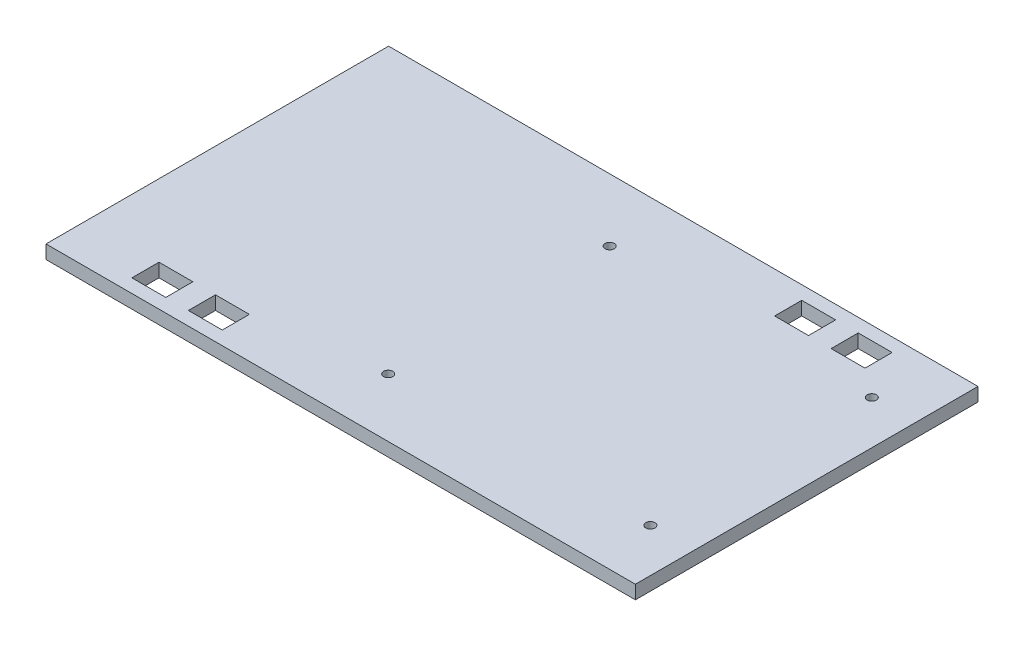
SolidWorks part; units mm, degrees
ref_plane "Front" through (0, 0, 0) normal (0, 0, 1) x (1, 0, 0)
ref_plane "Top" through (0, 0, 0) normal (0, 1, 0) x (1, 0, 0)
ref_plane "Right" through (0, 0, 0) normal (1, 0, 0) x (0, 0, -1)
sketch "Sketch1" plane through (0, 0, 0) normal (0, 1, 0) x (1, 0, 0)
  line L1 (0, 0) -> (130.41, 0)
  line L2 (0, 0) -> (0, -75.8)
  line L3 (0, -75.8) -> (130.41, -75.8)
  line L4 (130.41, 0) -> (130.41, -75.8)
  point P13 (0, 0)
  point P14 (0, 0)
  point P15 (0, 0)
  point P16 (0, 0)
  point P17 (0, 0)
  dimension "D1" = 130.41
  dimension "D2" = 75.8
extrude "Boss-Extrude1" add sketch "Sketch1" along normal blind 3 contours L2 L1 L4 L3
sketch "Sketch5" plane through (0, 0, 0) normal (0, -1, 0) x (1, 0, 0)
  line L0 (0, 75.8) -> (130.41, 75.8) construction
  line L1 (28.5, 72.8) -> (36, 72.8)
  line L2 (28.5, 72.8) -> (28.5, 66.8)
  line L3 (28.5, 66.8) -> (36, 66.8)
  line L4 (36, 72.8) -> (36, 66.8)
  line L6 (0, 0) -> (0, 75.8) construction
  line L7 (16, 72.8) -> (23.5, 72.8)
  line L8 (16, 72.8) -> (16, 66.8)
  line L9 (16, 66.8) -> (23.5, 66.8)
  line L10 (23.5, 72.8) -> (23.5, 66.8)
  dimension "D1" = 7.5
  dimension "D2" = 6
  dimension "D3" = 3
  dimension "D4" = 16
  dimension "D5" = 7.5
  dimension "D6" = 6
  dimension "D7" = 5
  dimension "D8" = 3
extrude "Cut-Extrude4" cut sketch "Sketch5" against normal through all
sketch "Sketch6" plane through (0, 0, 0) normal (0, -1, 0) x (1, 0, 0)
  line L0 (0, 0) -> (130.41, 0) construction
  line L1 (94.41, 9) -> (101.91, 9)
  line L2 (94.41, 9) -> (94.41, 3)
  line L3 (94.41, 3) -> (101.91, 3)
  line L4 (101.91, 9) -> (101.91, 3)
  line L6 (130.41, 0) -> (130.41, 75.8) construction
  line L7 (106.91, 9) -> (114.41, 9)
  line L8 (106.91, 9) -> (106.91, 3)
  line L9 (106.91, 3) -> (114.41, 3)
  line L10 (114.41, 9) -> (114.41, 3)
  dimension "D1" = 7.5
  dimension "D2" = 6
  dimension "D3" = 3
  dimension "D4" = 16
  dimension "D5" = 7.5
  dimension "D6" = 6
  dimension "D7" = 3
  dimension "D8" = 5
extrude "Cut-Extrude5" cut sketch "Sketch6" against normal through all
sketch "Sketch8" plane through (0, 0, 0) normal (0, -1, 0) x (1, 0, 0)
  line L2 (0, 75.8) -> (130.41, 75.8) construction
  line L3 (130.41, 0) -> (130.41, 75.8) construction
  circle A0 centre (120.77, 13.86) radius 1.025
  circle A1 centre (120.77, 62.86) radius 1.025
  dimension "D1" = 2.05
  dimension "D2" = 49
  dimension "D3" = 9.64
  dimension "D4" = 2.05
  dimension "D5" = 9.64
  dimension "D6" = 12.94
extrude "Cut-Extrude7" cut sketch "Sketch8" against normal through all
sketch "Sketch9" plane through (0, 0, 0) normal (0, -1, 0) x (1, 0, 0)
  line L1 (0, 0) -> (0, 75.8) construction
  line L2 (0, 75.8) -> (130.41, 75.8) construction
  circle A0 centre (62.77, 13.86) radius 1.025
  circle A1 centre (62.77, 62.86) radius 1.025
  dimension "D1" = 2.05
  dimension "D2" = 49
  dimension "D3" = 62.77
  dimension "D4" = 2.05
  dimension "D5" = 12.94
  dimension "D6" = 62.77
extrude "Cut-Extrude8" cut sketch "Sketch9" against normal through all
